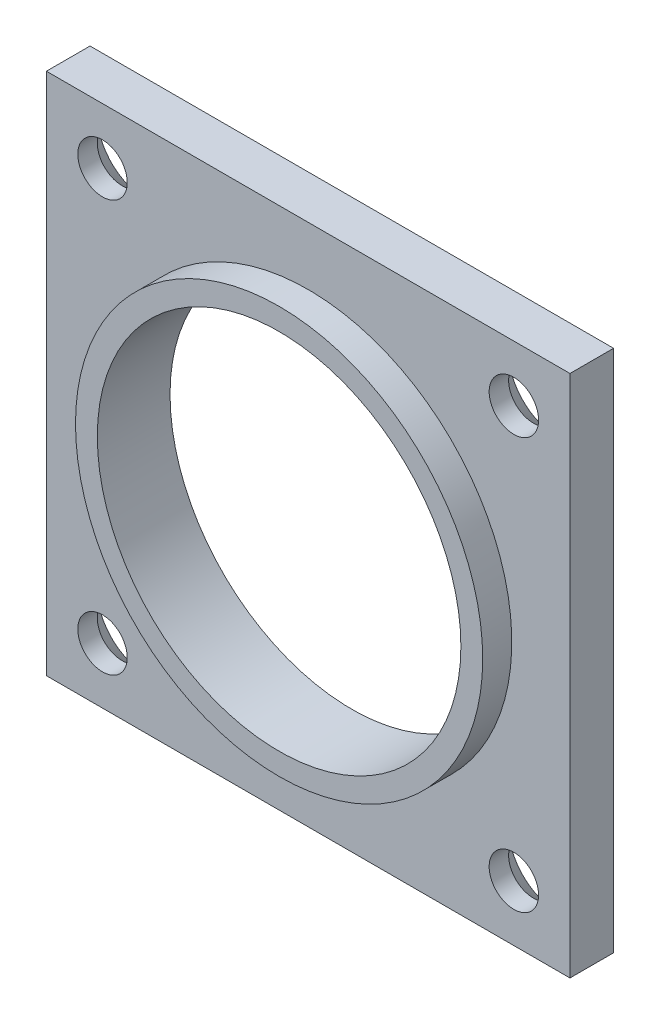
SolidWorks part; units mm, degrees
material "Liga 6061"
ref_plane "Plano frontal" through (0, 0, 0) normal (0, 0, 1) x (1, 0, 0)
ref_plane "Plano superior" through (0, 0, 0) normal (0, 1, 0) x (1, 0, 0)
ref_plane "Plano direito" through (0, 0, 0) normal (1, 0, 0) x (0, 0, -1)
sketch "Esboço1" plane through (0, 0, 0) normal (0, 0, 1) x (1, 0, 0)
  line L1 (-18, -18) -> (18, -18)
  line L2 (-18, -18) -> (-18, 18)
  line L3 (-18, 18) -> (18, 18)
  line L4 (18, -18) -> (18, 18)
  line L5 (-18, -18) -> (18, 18) construction
  line L6 (-18, 18) -> (18, -18) construction
  circle A0 centre (0, 0) radius 20 construction
  circle A2 centre (0, 0) radius 12.5
  point P0 (0, 0)
  dimension "D2" = 25
  dimension "D3" = 40
  dimension "D1" = 36
extrude "Ressalto-extrusão1" add sketch "Esboço1" along normal blind 3
sketch "Esboço2" plane through (0, 0, 3) normal (0, 0, 1) x (1, 0, 0)
  line L0 (0, 0) -> (19.0027, 19.0027) construction
  line L1 (0, 0) -> (8.8167, 0) construction
  circle A0 centre (0, 0) radius 14
  circle A1 centre (0, 0) radius 20 construction
  circle M5 centre (0, 0) radius 12.5
  dimension "D1" = 28
  dimension "D2" = 40
  dimension "D3" = 45
extrude "Ressalto-extrusão2" add sketch "Esboço2" along normal blind 2 contours A0 M5
hole_wizard "Escareado para SFHCS M32" positions "Esboço8" profile "Esboço9" countersink size "M3" standard "Ansi Metric" end condition through all
sketch "Esboço8" plane through (0, 0, 0) normal (0, 0, -1) x (-1, 0, 0)
  line L0 (0, 0) -> (-19.0027, 19.0027) construction
  circle A0 centre (0, 0) radius 20 construction
  point P0 (-14.1421, 14.1421)
  point P10 (14.1421, 14.1421)
  point P11 (14.1421, -14.1421)
  point P12 (-14.1421, -14.1421)
sketch "Esboço9" plane through (14.1421, 14.1421, 0) normal (1, 0, 0) x (0, 1, 0)
  line L0 (0, 0) -> (0, 5)
  line L1 (0, 5) -> (1.7, 5)
  line L2 (1.7, 5) -> (1.7, 1.66)
  line L3 (1.7, 1.66) -> (3.36, 0)
  line L5 (3.36, 0) -> (0, 0)
  line L6 (-1.7, 1.66) -> (-3.36, 0) construction
  line L11 (0, -6.35) -> (0, 107.95) construction
  dimension "Thru Hole Dia." = 3.4
  dimension "Thru Hole Depth" = 5
  dimension "Near C'Sink Dia." = 6.72
  dimension "Near C'Sink Angle" = 90
